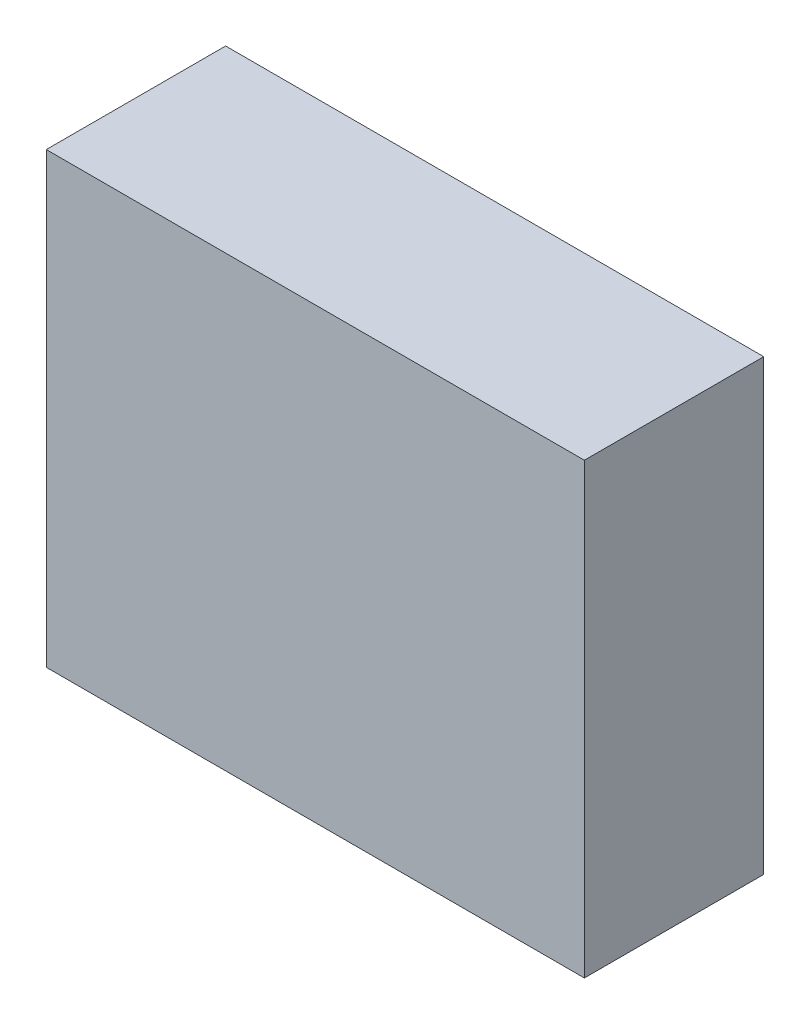
SolidWorks part; units mm, degrees
ref_plane "前视基准面" through (0, 0, 0) normal (0, 0, 1) x (1, 0, 0)
ref_plane "上视基准面" through (0, 0, 0) normal (0, 1, 0) x (1, 0, 0)
ref_plane "右视基准面" through (0, 0, 0) normal (1, 0, 0) x (0, 0, -1)
sketch "草图1" plane through (0, 0, 0) normal (0, 0, 1) x (1, 0, 0)
  line L1 (0, 0) -> (30, 0)
  line L2 (0, 0) -> (0, -25)
  line L3 (0, -25) -> (30, -25)
  line L4 (30, 0) -> (30, -25)
  dimension "D1" = 25
  dimension "D2" = 30
extrude "凸台-拉伸1" add sketch "草图1" along normal blind 10
